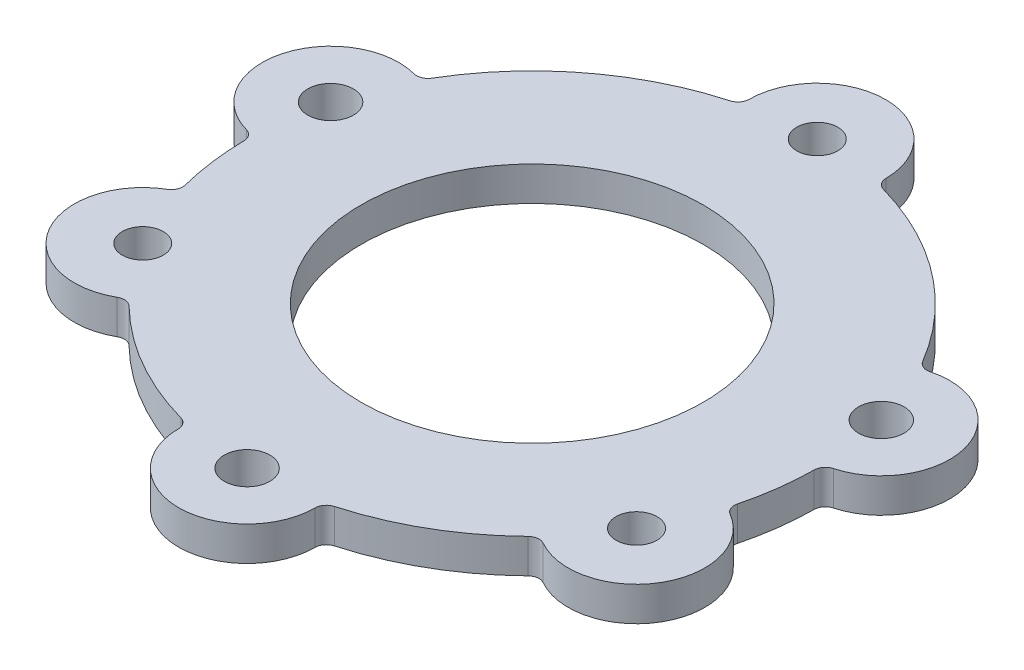
SolidWorks part; units mm, degrees
material "Delrin 2700 NC010, Low Viscosity Acetal Copolymer (SS)"
ref_plane "Front" through (0, 0, 0) normal (0, 0, 1) x (1, 0, 0)
ref_plane "Top" through (0, 0, 0) normal (0, 1, 0) x (1, 0, 0)
ref_plane "Right" through (0, 0, 0) normal (1, 0, 0) x (0, 0, -1)
sketch "Sketch1" plane through (0, 0, 0) normal (0, 1, 0) x (1, 0, 0)
  line L0 (-3, 0) -> (3, 0) construction
  line L5 (0, 0) -> (0, -12.5) construction
  line L8 (3, 0) -> (3, -12.5)
  line L9 (-3, 0) -> (-3, -12.5)
  line L12 (0, 0) -> (0, 12.5) construction
  line L15 (3, 0) -> (3, 12.5)
  line L18 (-3, 0) -> (-3, 12.5)
  line L21 (-1.5, -2.5981) -> (9.3253, -8.8481)
  line L24 (1.5, 2.5981) -> (12.3253, -3.6519)
  line L25 (0, 0) -> (10.8253, -6.25) construction
  line L26 (-1.5, 2.5981) -> (-12.3253, -3.6519)
  line L27 (1.5, -2.5981) -> (-9.3253, -8.8481)
  line L28 (0, 0) -> (-10.8253, -6.25) construction
  line L35 (0, 0) -> (-12.0741, 3.2352) construction
  line L36 (-0.7765, -2.8978) -> (-12.8505, 0.3375)
  line L37 (0.7765, 2.8978) -> (-11.2976, 6.133)
  line L38 (0, 25.1874) -> (0, -25.1874) construction
  line L39 (0, 0) -> (12.0741, 3.2352) construction
  line L40 (0.7765, -2.8978) -> (12.8505, 0.3375)
  line L41 (-0.7765, 2.8978) -> (11.2976, 6.133)
  circle A1 centre (0, 0) radius 7.5
  arc A11 (3, 0) -> (-3, 0) centre (0, 0) ccw
  arc A12 (-3, -12.5) -> (3, -12.5) centre (0, -12.5) ccw
  circle A13 centre (0, -12.5) radius 1
  circle A21 centre (0, 0) radius 12.5
  arc A22 (3, 0) -> (-3, 0) centre (0, 0) cw
  arc A23 (-3, 12.5) -> (3, 12.5) centre (0, 12.5) cw
  circle A24 centre (0, 12.5) radius 0.9
  arc A25 (12.3253, -3.6519) -> (9.3253, -8.8481) centre (10.8253, -6.25) cw
  arc A26 (-1.5, -2.5981) -> (1.5, 2.5981) centre (0, 0) cw
  circle A27 centre (10.8253, -6.25) radius 0.9
  arc A28 (-9.3253, -8.8481) -> (-12.3253, -3.6519) centre (-10.8253, -6.25) cw
  arc A29 (-1.5, 2.5981) -> (1.5, -2.5981) centre (0, 0) cw
  circle A30 centre (-10.8253, -6.25) radius 0.9
  arc A31 (-0.7765, -2.8978) -> (0.7765, 2.8978) centre (0, 0) ccw
  arc A32 (-11.2976, 6.133) -> (-12.8505, 0.3375) centre (-12.0741, 3.2352) ccw
  circle A33 centre (-12.0741, 3.2352) radius 1
  circle A35 centre (12.0741, 3.2352) radius 1
  arc A36 (0.7765, -2.8978) -> (-0.7765, 2.8978) centre (0, 0) cw
  arc A37 (11.2976, 6.133) -> (12.8505, 0.3375) centre (12.0741, 3.2352) cw
  point P7 (0, 6.25)
  point P10 (0, -6.25)
  point P20 (-6.037, 1.6176)
  point P25 (-5.4127, -3.125)
  point P27 (5.4127, -3.125)
  point P30 (0, -15.5)
  point P37 (-5.4127, -3.125)
  point P38 (-5.4127, 3.125)
  point P52 (0, 0)
  point P55 (6.037, 1.6176)
  point P71 (-5.4127, -3.125)
  point P78 (-5.4127, 3.125)
  dimension "D2" = 15
  dimension "D6" = 3
  dimension "D7" = 2
  dimension "D5" = 25
  dimension "D1" = 1.8
  dimension "D4" = 2
  dimension "D8" = 12.5
  dimension "D3" = 75
extrude "Boss-Extrude1" add sketch "Sketch1" along normal blind 1.5 contours A24 A21 L15 A23 L18 | A24 A21 L18 A1 L15 | L41 A21 L15 A1 | A21 A35 L41 A1 L24 L40 | A37 L41 A21 A35 L40 | L24 A21 L40 | A1 L40 L24 | A27 A21 L24 L40 A1 L21 | A27 A21 L21 A25 L24 | L8 A21 L21 A1 | A13 A21 L8 A1 L9 | A21 A13 L9 A12 L8 | L27 A21 L9 A1 | A30 A21 L27 A1 L36 L26 | A30 A21 L26 A28 L27 | A1 L26 L36 | L36 A21 L26 | A33 A21 L36 L26 A1 L37 | A33 A21 L37 A32 L36 | L18 A21 L37 A1
fillet "Fillet1" radius 0.5 12 edges at (-3, 0.75, 12.1347) (3, 0.75, 12.1347) (9.0089, 0.75, 8.6654) (12.0089, 0.75, 3.4693) (12.4976, 0.75, -0.2429) (10.9447, 0.75, -6.0385) (3, 0.75, -12.1347) (-3, 0.75, -12.1347) (-10.9447, 0.75, -6.0385) (-12.4976, 0.75, -0.2429) (-12.0089, 0.75, 3.4693) (-9.0089, 0.75, 8.6654)
equation "\"PostAngle\"=75"
equation "\"D3@Sketch1\"=\"PostAngle\""
